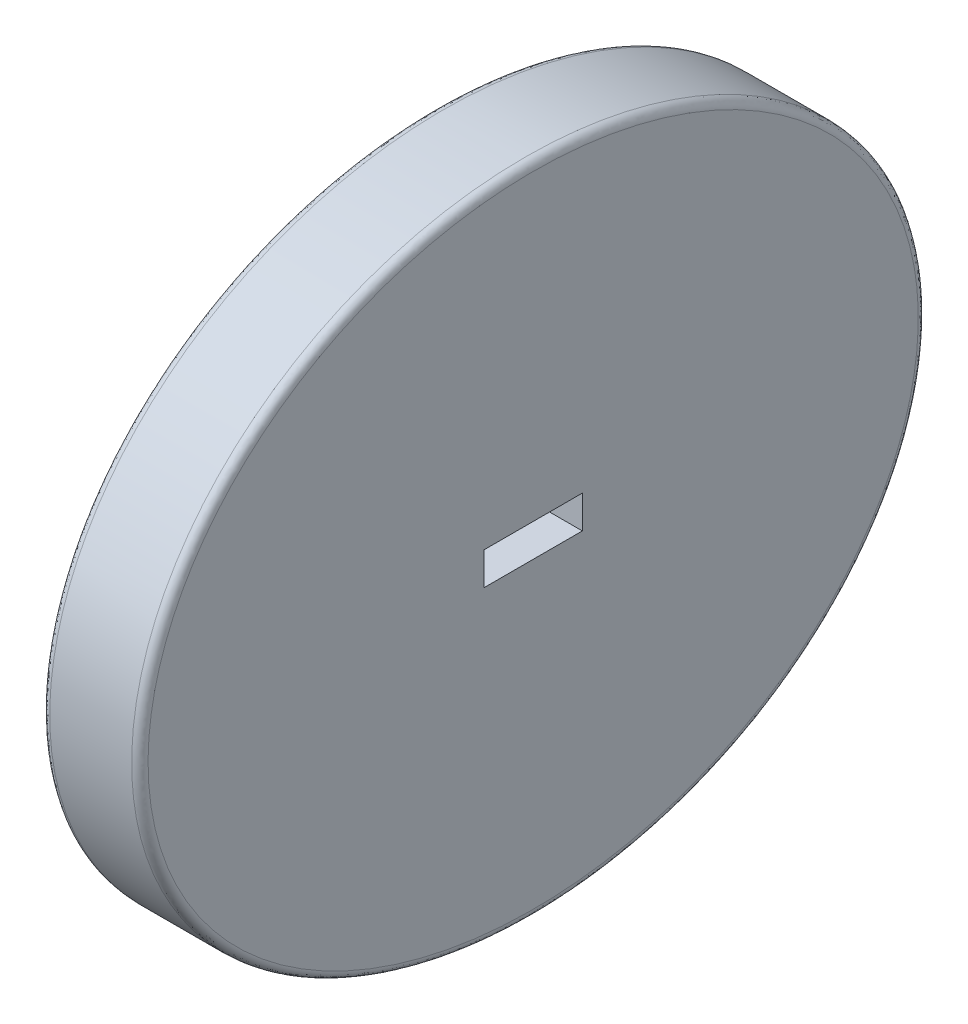
SolidWorks part; units mm, degrees
material "Alloy Steel"
ref_plane "Front Plane" through (0, 0, 0) normal (0, 0, 1) x (1, 0, 0)
ref_plane "Top Plane" through (0, 0, 0) normal (0, 1, 0) x (1, 0, 0)
ref_plane "Right Plane" through (0, 0, 0) normal (1, 0, 0) x (0, 0, -1)
sketch "Sketch1" plane through (0, 0, 0) normal (1, 0, 0) x (0, 0, -1)
  line L3 (-9.525, -3.175) -> (9.525, -3.175)
  line L4 (-9.525, -3.175) -> (-9.525, 3.175)
  line L5 (-9.525, 3.175) -> (9.525, 3.175)
  line L6 (9.525, -3.175) -> (9.525, 3.175)
  line L7 (-9.525, -3.175) -> (9.525, 3.175) construction
  line L8 (-9.525, 3.175) -> (9.525, -3.175) construction
  ellipse E0 centre (0, 0) end of major axis (76.2, 0) minor radius 63.5
  point P10 (0, 0)
  point P12 (0, 0)
  dimension "D1" = 76.2
  dimension "D2" = 63.5
  dimension "D3" = 19.05
  dimension "D4" = 6.35
extrude "Boss-Extrude1" add sketch "Sketch1" along normal blind 19.05
fillet "Fillet1" radius 1.5875 2 edges at (0, 0, -76.2) (19.05, 0, -76.2)
